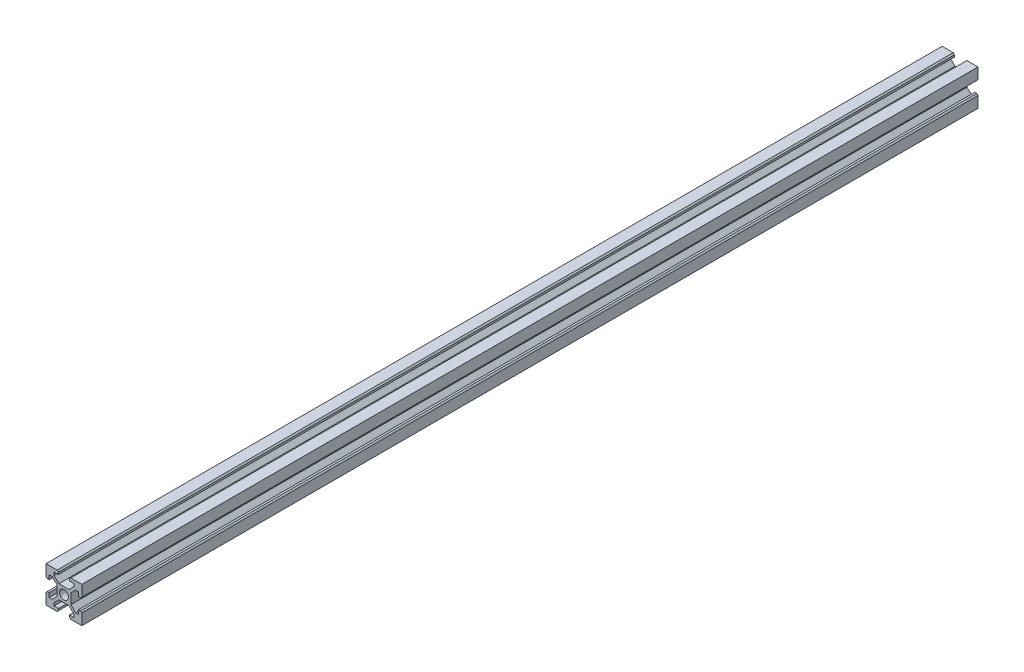
SolidWorks part; units mm, degrees
material "1060 Alloy"
ref_plane "Front Plane" through (0, 0, 0) normal (0, 0, 1) x (1, 0, 0)
ref_plane "Top Plane" through (0, 0, 0) normal (0, 1, 0) x (1, 0, 0)
ref_plane "Right Plane" through (0, 0, 0) normal (1, 0, 0) x (0, 0, -1)
sketch "Sketch1" plane through (0, 0, 0) normal (0, 0, 1) x (1, 0, 0)
  line L0 (3.9, -2.8393) -> (6.5607, -5.5)
  line L1 (-10, 10) -> (10, 10) construction
  line L2 (-10, 10) -> (-10, -10) construction
  line L3 (-10, -10) -> (10, -10) construction
  line L4 (10, 10) -> (10, -10) construction
  line L5 (-10, 10) -> (10, -10) construction
  line L6 (-10, -10) -> (10, 10) construction
  line L7 (-3.9, -3.9) -> (3.9, -3.9) construction
  line L8 (-3.9, -3.9) -> (-3.9, 3.9) construction
  line L9 (-3.9, 3.9) -> (3.9, 3.9) construction
  line L10 (3.9, -3.9) -> (3.9, 3.9) construction
  line L11 (-3.9, -3.9) -> (3.9, 3.9) construction
  line L12 (-3.9, 3.9) -> (3.9, -3.9) construction
  line L13 (-10, 10) -> (-5.5, 10) construction
  line L14 (-10, 10) -> (-10, 5.5) construction
  line L15 (-10, 5.5) -> (-5.5, 5.5) construction
  line L16 (-5.5, 10) -> (-5.5, 5.5) construction
  line L17 (10, 10) -> (5.5, 10) construction
  line L18 (10, 10) -> (10, 5.5) construction
  line L19 (10, 5.5) -> (5.5, 5.5) construction
  line L20 (5.5, 10) -> (5.5, 5.5) construction
  line L21 (-10, -10) -> (-5.5, -10) construction
  line L22 (-10, -10) -> (-10, -5.5) construction
  line L23 (-10, -5.5) -> (-5.5, -5.5) construction
  line L24 (-5.5, -10) -> (-5.5, -5.5) construction
  line L25 (10, -10) -> (5.5, -10) construction
  line L26 (10, -10) -> (10, -5.5) construction
  line L27 (10, -5.5) -> (5.5, -5.5) construction
  line L28 (5.5, -10) -> (5.5, -5.5) construction
  line L29 (2.8393, -3.9) -> (5.5, -6.5607)
  line L30 (-5.5, 6.5607) -> (-2.8393, 3.9)
  line L31 (-6.5607, 5.5) -> (-3.9, 2.8393)
  line L32 (5.5, 6.5607) -> (2.8393, 3.9)
  line L33 (6.5607, 5.5) -> (3.9, 2.8393)
  line L34 (-6.5607, -5.5) -> (-3.9, -2.8393)
  line L35 (-5.5, -6.5607) -> (-2.8393, -3.9)
  line L36 (-2.8393, 3.9) -> (2.8393, 3.9)
  line L37 (-3.9, 2.8393) -> (-3.9, -2.8393)
  line L38 (-2.8393, -3.9) -> (2.8393, -3.9)
  line L39 (3.9, -2.8393) -> (3.9, 2.8393)
  line L40 (5.5, 6.5607) -> (5.5, 8.2007)
  line L41 (5.5, 8.2007) -> (3.1, 8.2007)
  line L42 (3.1, 8.2007) -> (3.1, 9.3)
  line L43 (3.1, 9.3) -> (3.8, 10)
  line L44 (3.8, 10) -> (10, 10)
  line L45 (10, 10) -> (10, 3.8)
  line L46 (10, 3.8) -> (9.3, 3.1)
  line L47 (9.3, 3.1) -> (8.2007, 3.1)
  line L48 (8.2007, 3.1) -> (8.2007, 5.5)
  line L49 (8.2007, 5.5) -> (6.5607, 5.5)
  line L50 (3.1, -8.2007) -> (5.5, -8.2007)
  line L51 (3.1, -9.3) -> (3.1, -8.2007)
  line L52 (3.8, -10) -> (3.1, -9.3)
  line L53 (10, -10) -> (3.8, -10)
  line L54 (10, -3.8) -> (10, -10)
  line L55 (9.3, -3.1) -> (10, -3.8)
  line L56 (8.2007, -3.1) -> (9.3, -3.1)
  line L57 (8.2007, -5.5) -> (8.2007, -3.1)
  line L58 (6.5607, -5.5) -> (8.2007, -5.5)
  line L59 (5.5, -8.2007) -> (5.5, -6.5607)
  line L60 (-8.2007, -3.1) -> (-8.2007, -5.5)
  line L61 (-9.3, -3.1) -> (-8.2007, -3.1)
  line L62 (-10, -3.8) -> (-9.3, -3.1)
  line L63 (-10, -10) -> (-10, -3.8)
  line L64 (-3.8, -10) -> (-10, -10)
  line L65 (-3.1, -9.3) -> (-3.8, -10)
  line L66 (-3.1, -8.2007) -> (-3.1, -9.3)
  line L67 (-5.5, -8.2007) -> (-3.1, -8.2007)
  line L68 (-5.5, -6.5607) -> (-5.5, -8.2007)
  line L69 (-8.2007, -5.5) -> (-6.5607, -5.5)
  line L70 (-3.1, 8.2007) -> (-5.5, 8.2007)
  line L71 (-3.1, 9.3) -> (-3.1, 8.2007)
  line L72 (-3.8, 10) -> (-3.1, 9.3)
  line L73 (-10, 10) -> (-3.8, 10)
  line L74 (-10, 3.8) -> (-10, 10)
  line L75 (-9.3, 3.1) -> (-10, 3.8)
  line L76 (-8.2007, 3.1) -> (-9.3, 3.1)
  line L77 (-8.2007, 5.5) -> (-8.2007, 3.1)
  line L78 (-6.5607, 5.5) -> (-8.2007, 5.5)
  line L79 (-5.5, 8.2007) -> (-5.5, 6.5607)
  circle A0 centre (0, 0) radius 2.5
  point P83 (0, 0)
  dimension "D1" = 5
  dimension "D2" = 20
  dimension "D3" = 7.8
  dimension "D4" = 4.5
  dimension "D5" = 1.5
  dimension "D6" = 0.75
  dimension "D7" = 1.5
  dimension "D8" = 0.75
  dimension "D9" = 1.5
  dimension "D10" = 0.75
  dimension "D11" = 1.5
  dimension "D12" = 0.75
  dimension "D13" = 1.64
  dimension "D14" = 45
  dimension "D15" = 3.1
  dimension "D16" = 6.2
  dimension "D17" = 6.2
  dimension "D18" = 3.1
  dimension "D19" = 4
extrude "Boss-Extrude1" add sketch "Sketch1" along normal mid plane 500 contours L79 L70 L71 L72 L73 L74 L75 L76 L77 L78 L31 L37 L34 L69 L60 L61 L62 L63 L64 L65 L66 L67 L68 L35 L38 L29 L59 L50 L51 L52 L53 L54 L55 L56 L57 L58 L0 L39 L33 L49 L48 L47 L46 L45 L44 L43 L42 L41 L40 L32 L36
